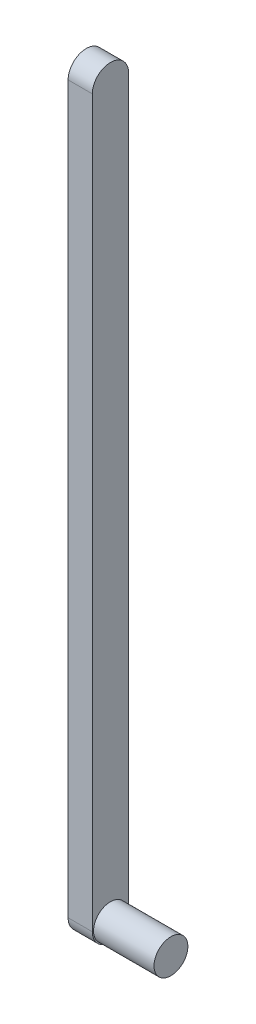
SolidWorks part; units mm, degrees
ref_plane "Front Plane" through (0, 0, 0) normal (0, 0, 1) x (1, 0, 0)
ref_plane "Top Plane" through (0, 0, 0) normal (0, 1, 0) x (1, 0, 0)
ref_plane "Right Plane" through (0, 0, 0) normal (1, 0, 0) x (0, 0, -1)
sketch "Sketch1" plane through (0, 0, 0) normal (1, 0, 0) x (0, 0, -1)
  line L0 (0, 0) -> (0, 60) construction
  line L1 (-1.5, 0) -> (-1.5, 60)
  line L2 (1.5, 0) -> (1.5, 60)
  arc A0 (-1.5, 0) -> (1.5, 0) centre (0, 0) ccw
  arc A1 (1.5, 60) -> (-1.5, 60) centre (0, 60) ccw
  point P3 (0, 30)
  dimension "D1" = 3
  dimension "D2" = 60
extrude "Boss-Extrude1" add sketch "Sketch1" along normal blind 2
sketch "Sketch3" plane through (2, 0, 0) normal (1, 0, 0) x (0, 0, -1)
  circle A0 centre (0, 0) radius 1.4
  dimension "D1" = 2.8
extrude "Boss-Extrude3" add sketch "Sketch3" along normal blind 5
